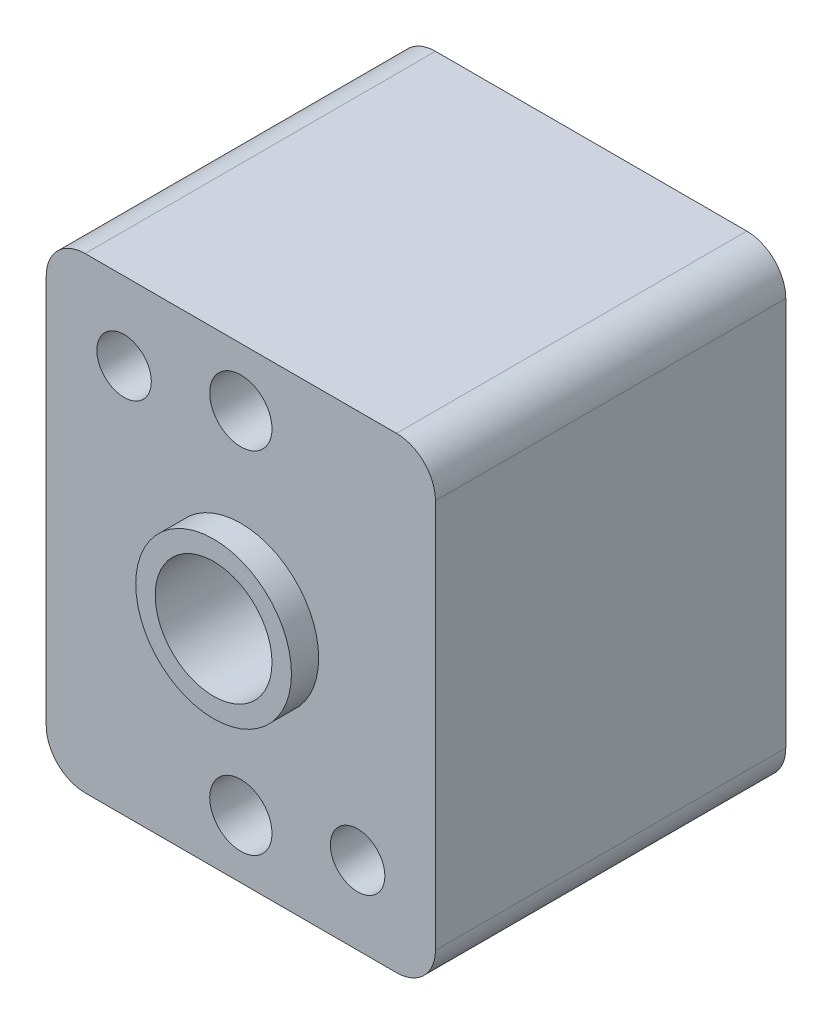
SolidWorks part; units mm, degrees
ref_plane "前视基准面" through (0, 0, 0) normal (0, 0, 1) x (1, 0, 0)
ref_plane "上视基准面" through (0, 0, 0) normal (0, 1, 0) x (1, 0, 0)
ref_plane "右视基准面" through (0, 0, 0) normal (1, 0, 0) x (0, 0, -1)
sketch "草图1" plane through (0, 0, 0) normal (0, 0, 1) x (1, 0, 0)
  line L0 (0, 0) -> (-50000, 0) construction
  line L1 (-5, -6) -> (5, -6)
  line L2 (-5, -6) -> (-5, 6)
  line L3 (-5, 6) -> (5, 6)
  line L4 (5, -6) -> (5, 6)
  line L5 (-5, -6) -> (5, 6) construction
  line L6 (-5, 6) -> (5, -6) construction
  line L7 (0, 0) -> (0, 7.3369) construction
  circle A0 centre (0, 0) radius 1.5
  circle A1 centre (0, 4.5) radius 0.8
  circle A2 centre (0, -4.5) radius 0.8
  circle A3 centre (-3, 4) radius 0.7
  circle A5 centre (3, -4) radius 0.7
  point P0 (0, 0)
  point P18 (-2.9989, 4.0635)
  dimension "D3" = 3
  dimension "D4" = 9
  dimension "D5" = 1.6
  dimension "D6" = 3
  dimension "D7" = 4
  dimension "D8" = 1.4
  dimension "D1" = 10
  dimension "D2" = 12
extrude "凸台-拉伸1" add sketch "草图1" along normal blind 9
sketch "草图2" plane through (0, 0, 9) normal (0, 0, 1) x (1, 0, 0)
  circle A0 centre (0, 0) radius 2
  circle A1 centre (0, 0) radius 1.5
extrude "凸台-拉伸2" add sketch "草图2" along normal blind 0.7
fillet "圆角1" radius 1 4 edges at (5, 6, 4.5) (-5, 6, 4.5) (-5, -6, 4.5) (5, -6, 4.5)
